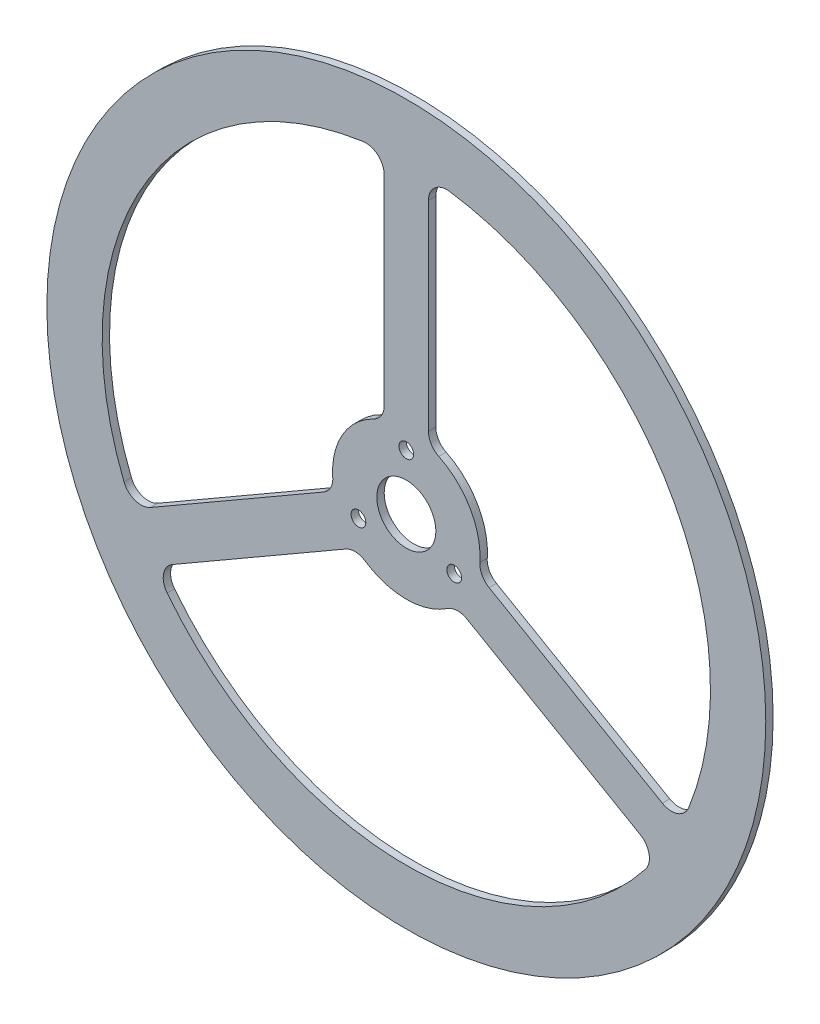
SolidWorks part; units mm, degrees
ref_plane "Front" through (0, 0, 0) normal (0, 0, 1) x (1, 0, 0)
ref_plane "Top" through (0, 0, 0) normal (0, 1, 0) x (1, 0, 0)
ref_plane "Right" through (0, 0, 0) normal (1, 0, 0) x (0, 0, -1)
sketch "草图1" plane through (0, 0, 0) normal (0, 0, 1) x (1, 0, 0)
  circle A0 centre (0, 0) radius 97.5
  dimension "D1" = 195
extrude "凸台-拉伸1" add sketch "草图1" along normal blind 2
sketch "草图2" plane through (0, 0, 0) normal (0, 0, -1) x (-1, 0, 0)
  line L0 (0, 100.9008) -> (0, -122.4148) construction
  line L1 (-6, 22.4499) -> (-6, 76.7154)
  line L2 (6, 22.4499) -> (6, 76.7154)
  line L3 (22.4422, -6.0288) -> (69.4375, -33.1615)
  line L4 (16.4422, -16.4211) -> (63.4375, -43.5538)
  line L5 (-16.4422, -16.4211) -> (-63.4375, -43.5538)
  line L6 (-22.4422, -6.0288) -> (-69.4375, -33.1615)
  arc A0 (-11.7097, 81.6648) -> (-76.5786, -30.6915) centre (0, 0) ccw
  arc A1 (-8.8, 17.96) -> (-19.9538, -1.359) centre (0, 0) ccw
  arc A2 (-64.8689, -50.9733) -> (64.8689, -50.9733) centre (0, 0) ccw
  arc A3 (76.5786, -30.6915) -> (11.7097, 81.6648) centre (0, 0) ccw
  arc A4 (-11.1538, -16.601) -> (11.1538, -16.601) centre (0, 0) ccw
  arc A5 (19.9538, -1.359) -> (8.8, 17.96) centre (0, 0) ccw
  arc A6 (-8.8, 17.96) -> (-6, 22.4499) centre (-11, 22.4499) ccw
  arc A7 (-19.9538, -1.359) -> (-22.4422, -6.0288) centre (-24.9422, -1.6987) cw
  arc A8 (-11.1538, -16.601) -> (-16.4422, -16.4211) centre (-13.9422, -20.7513) ccw
  arc A9 (11.1538, -16.601) -> (16.4422, -16.4211) centre (13.9422, -20.7513) cw
  arc A10 (22.4422, -6.0288) -> (19.9538, -1.359) centre (24.9422, -1.6987) cw
  arc A11 (8.8, 17.96) -> (6, 22.4499) centre (11, 22.4499) cw
  arc A12 (64.8689, -50.9733) -> (63.4375, -43.5538) centre (60.9375, -47.884) ccw
  arc A13 (69.4375, -33.1615) -> (76.5786, -30.6915) centre (71.9375, -28.8314) ccw
  arc A14 (-64.8689, -50.9733) -> (-63.4375, -43.5538) centre (-60.9375, -47.884) cw
  arc A15 (-76.5786, -30.6915) -> (-69.4375, -33.1615) centre (-71.9375, -28.8314) ccw
  arc A16 (6, 76.7154) -> (11.7097, 81.6648) centre (11, 76.7154) cw
  arc A17 (-6, 76.7154) -> (-11.7097, 81.6648) centre (-11, 76.7154) ccw
  circle A18 centre (0, 0) radius 8
  point P20 (0, 0)
  point P39 (6, 82.2815)
  point P42 (-6, 82.2815)
  dimension "D1" = 165
  dimension "D2" = 40
  dimension "D5" = 5
  dimension "D6" = 16
  dimension "D3" = 6
  dimension "D4" = 3
extrude "切除-拉伸1" cut sketch "草图2" against normal through all
sketch "草图3" plane through (0, 0, 0) normal (0, 0, -1) x (-1, 0, 0)
  circle A0 centre (0, 15) radius 2
  dimension "D1" = 15
extrude "切除-拉伸2" cut sketch "草图3" against normal through all
pattern_circular "阵列(圆周)1" count 3 over 360 about axis through (0, 0, 0) along (0, 0, 1) of "切除-拉伸2"
